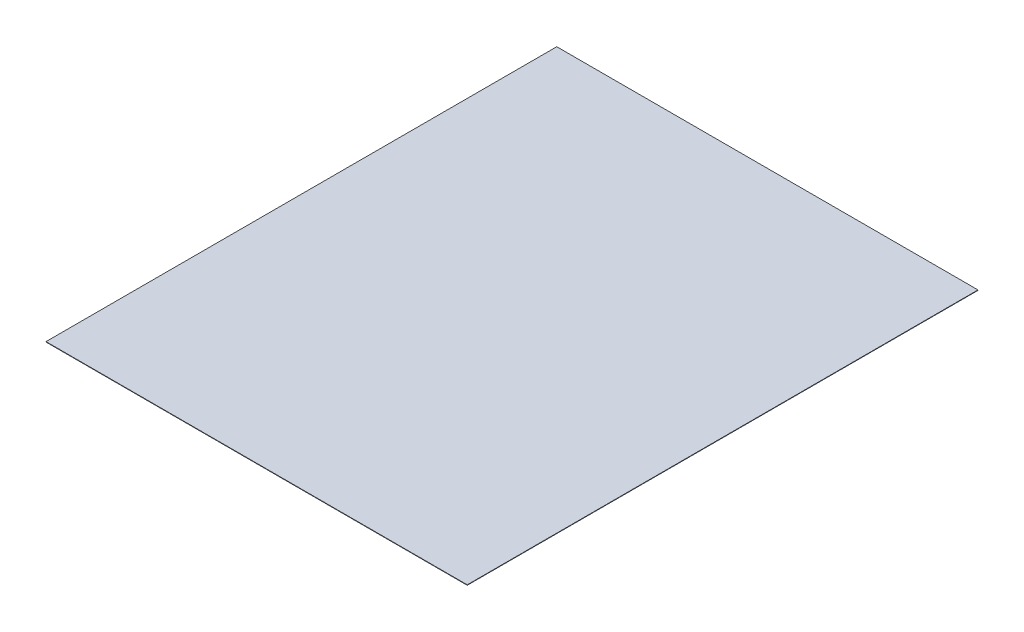
SolidWorks part; units mm, degrees
ref_plane "Спереди" through (0, 0, 0) normal (0, 0, 1) x (1, 0, 0)
ref_plane "Сверху" through (0, 0, 0) normal (0, 1, 0) x (1, 0, 0)
ref_plane "Справа" through (0, 0, 0) normal (1, 0, 0) x (0, 0, -1)
other "Configuration Table"
sketch "Эскиз1" plane through (0, 0, 0) normal (0, 1, 0) x (1, 0, 0)
  line L1 (500, 606.25) -> (-500, 606.25)
  line L2 (500, 606.25) -> (500, -606.25)
  line L3 (500, -606.25) -> (-500, -606.25)
  line L4 (-500, 606.25) -> (-500, -606.25)
  line L5 (500, 606.25) -> (-500, -606.25) construction
  line L6 (500, -606.25) -> (-500, 606.25) construction
  point P0 (0, 0)
extrude "Бобышка-Вытянуть1" add sketch "Эскиз1" along normal blind 1
